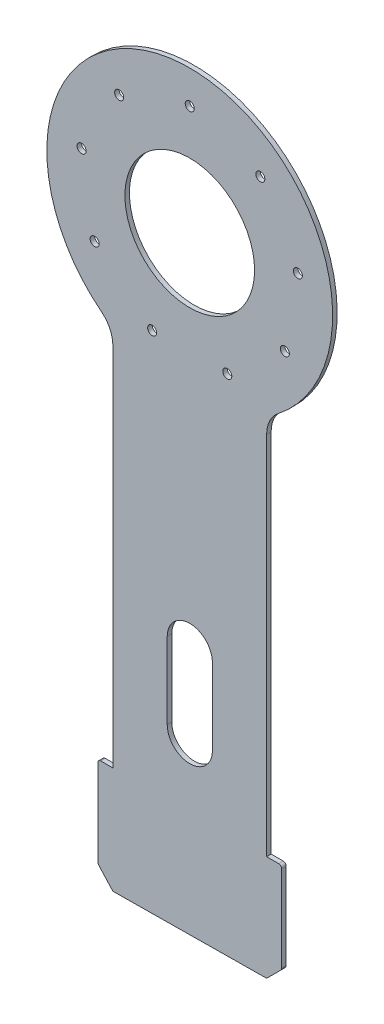
SolidWorks part; units mm, degrees
ref_plane "Front Plane" through (0, 0, 0) normal (0, 0, 1) x (1, 0, 0)
ref_plane "Top Plane" through (0, 0, 0) normal (0, 1, 0) x (1, 0, 0)
ref_plane "Right Plane" through (0, 0, 0) normal (1, 0, 0) x (0, 0, -1)
sketch "Sketch1" plane through (0, 0, 0) normal (0, 0, 1) x (1, 0, 0)
  circle A0 centre (0, 0) radius 47.5
  circle A1 centre (0, 0) radius 21.55
  dimension "D1" = 95
  dimension "D2" = 43.1
extrude "Boss-Extrude1" add sketch "Sketch1" along normal blind 1.5
sketch "Sketch2" plane through (0, 0, 1.5) normal (0, 0, 1) x (1, 0, 0)
  circle A0 centre (0, 0) radius 36.5 construction
  dimension "D1" = 73
sketch "Sketch3" plane through (0, 0, 1.5) normal (0, 0, 1) x (1, 0, 0)
  circle A0 centre (0, 36.5) radius 1.5
  circle A1 centre (0, 0) radius 36.5 construction
  point P0 (0, 36.5)
  dimension "D1" = 3
hole_wizard "Ø3.0mm Dowel Hole1" positions "Sketch3" profile "Sketch4" hole size "Ø3.0" standard "ANSI Metric" end condition through all
sketch "Sketch4" plane through (0, 36.5, 1.5) normal (1, 0, 0) x (0, -1, 0)
  line L0 (0, 0) -> (0, 1.5)
  line L1 (0, 1.5) -> (1.5, 1.5)
  line L2 (1.5, 1.5) -> (1.5, 0)
  line L5 (1.5, 0) -> (0, 0)
  line L11 (0, -6.35) -> (0, 107.95) construction
  dimension "Thru Hole Dia." = 3
  dimension "Thru Hole Depth" = 1.5
pattern_circular "CirPattern1" count 9 over 360 about axis through (0, 0, 0) along (0, 0, 1) of "Ø3.0mm Dowel Hole1"
sketch "Sketch6" plane through (0, 0, 1.5) normal (0, 0, 1) x (1, 0, 0)
  line L0 (0, -47.5) -> (0, -40.0345) construction
  line L1 (0, -40.0345) -> (-25.5634, -40.0345) construction
  line L2 (-25.5634, -40.0345) -> (25.5634, -40.0345) construction
  line L3 (-25.5634, -40.0345) -> (25.5634, -40.0345)
  line L4 (-25.5634, -40.0345) -> (-25.5634, -166.7845)
  line L5 (-25.5634, -166.7845) -> (-30.5634, -166.7845)
  line L6 (-30.5634, -166.7845) -> (-30.5634, -196.7845)
  line L7 (-30.5634, -196.7845) -> (-25.5634, -202.2868)
  line L8 (30.5634, -166.7745) -> (30.5634, -196.7845)
  line L9 (25.5634, -40.0345) -> (25.5634, -166.7745)
  line L10 (25.5634, -166.7745) -> (30.5634, -166.7745)
  line L11 (30.5634, -196.7845) -> (25.5634, -201.7845)
  line L12 (25.5634, -201.7845) -> (-25.5634, -202.2868)
  circle A1 centre (0, 0) radius 47.5 construction
extrude "Boss-Extrude2" add sketch "Sketch6" against normal blind 1.5
fillet "Fillet7" radius 10 1 edges at (-25.5634, -40.0345, 0.75)
fillet "Fillet8" radius 10 1 edges at (25.5634, -40.0345, 0.75)
fillet "Fillet9" radius 1 2 edges at (-30.5634, -166.7845, 0.75) (30.5634, -166.7745, 0.75)
fillet "Fillet10" radius 1 4 edges at (-30.5634, -196.7845, 0.75) (-25.5634, -202.2868, 0.75) (25.5634, -201.7845, 0.75) (30.5634, -196.7845, 0.75)
sketch "Sketch8" plane through (0, 0, 0) normal (0, 0, -1) x (-1, 0, 0)
  line L0 (-0.02, -202.0354) -> (-0.02, -145.2854) construction
  line L1 (25.1151, -202.2824) -> (-25.155, -201.7885) construction
  line L2 (-0.02, -145.2854) -> (-0.02, -119.8854) construction
  line L3 (-7.52, -145.2854) -> (-7.52, -119.8854)
  line L4 (7.48, -145.2854) -> (7.48, -119.8854)
  arc A0 (-7.52, -145.2854) -> (7.48, -145.2854) centre (-0.02, -145.2854) ccw
  arc A1 (7.48, -119.8854) -> (-7.52, -119.8854) centre (-0.02, -119.8854) ccw
  point P4 (-0.02, -132.5854)
extrude "Cut-Extrude2" cut sketch "Sketch8" against normal blind 1.5
